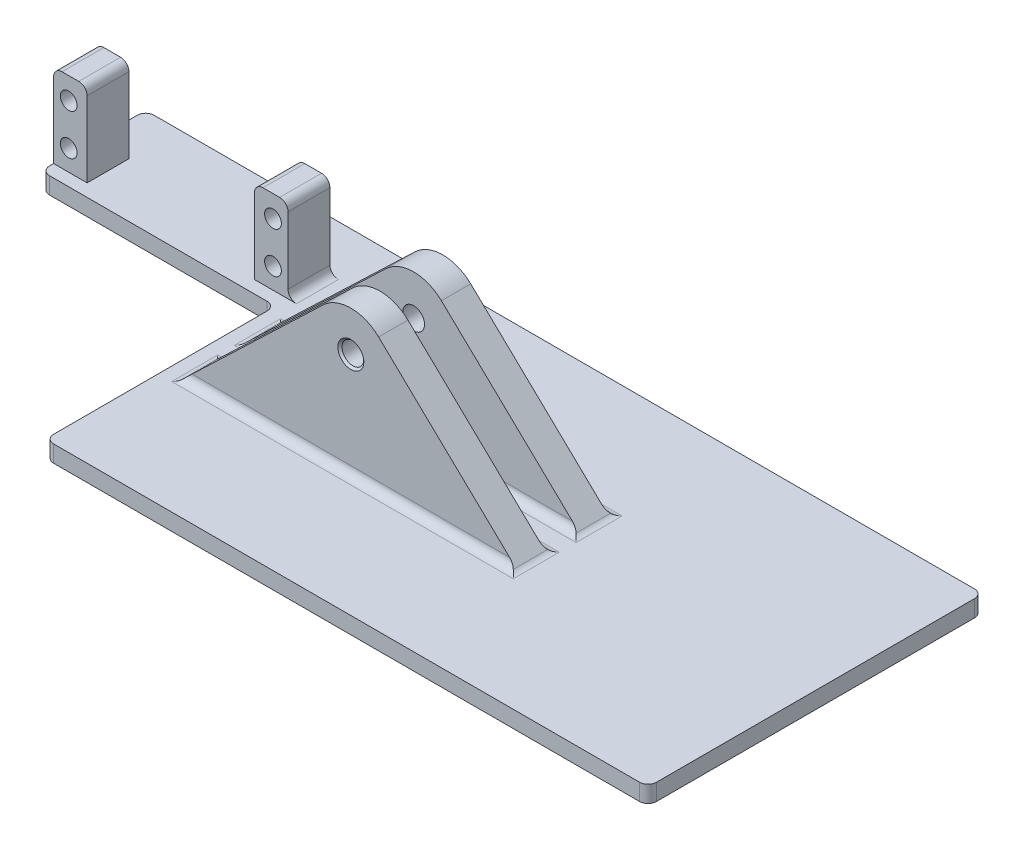
SolidWorks part; units mm, degrees
ref_plane "Front Plane" through (0, 0, 0) normal (0, 0, 1) x (1, 0, 0)
ref_plane "Top Plane" through (0, 0, 0) normal (0, 1, 0) x (1, 0, 0)
ref_plane "Right Plane" through (0, 0, 0) normal (1, 0, 0) x (0, 0, -1)
sketch "Sketch1" plane through (0, 0, 0) normal (0, 0, 1) x (1, 0, 0)
  line L0 (-6.6383, 6.9349) -> (-40, -25)
  line L1 (-40, -25) -> (40, -25)
  line L2 (40, -25) -> (6.6383, 6.9349)
  circle A0 centre (0, 0) radius 2.6
  arc A1 (6.6383, 6.9349) -> (-6.6383, 6.9349) centre (0, 0) ccw
  point P6 (0, -25)
  dimension "D1" = 5.2
  dimension "D2" = 7
  dimension "D3" = 80
  dimension "D4" = 25
extrude "Boss-Extrude1" add sketch "Sketch1" along normal blind 22
sketch "Sketch2" plane through (0, -25, 0) normal (0, -1, 0) x (-1, 0, 0)
  line L0 (-40, -22) -> (-40, 0) construction
  line L1 (-100, -51) -> (100, -51)
  line L2 (-100, -51) -> (-100, 29)
  line L3 (-100, 29) -> (100, 29)
  line L4 (100, -51) -> (100, 29)
  point P6 (-40, -11)
  point P7 (-100, -11)
  point P9 (0, 29)
  dimension "D1" = 200
  dimension "D2" = 80
extrude "Boss-Extrude2" add sketch "Sketch2" along normal blind 4
sketch "Sketch3" plane through (100, 0, 0) normal (1, 0, 0) x (0, 0, -1)
  line L0 (29, -25) -> (-51, -25) construction
  line L1 (-15, -25) -> (-7, -25)
  line L2 (-15, -25) -> (-15, 10)
  line L3 (-15, 10) -> (-7, 10)
  line L4 (-7, -25) -> (-7, 10)
  line L5 (0, -25) -> (0, 6.9349) construction
  dimension "D1" = 8
  dimension "D2" = 7
  dimension "D3" = 35
extrude "Cut-Extrude1" cut sketch "Sketch3" against normal through all
chamfer "Chamfer1" distance 0.5 angle 45 2 edges at (2.6, 0, 22) (2.6, 0, 0)
sketch "Sketch4" plane through (0, 0, -29) normal (0, 0, -1) x (-1, 0, 0)
  line L0 (72, -25) -> (72, 2.2972) construction
  line L1 (100, -25) -> (92, -25)
  line L2 (100, -25) -> (100, -5)
  line L3 (100, -5) -> (92, -5)
  line L4 (92, -25) -> (92, -5)
  line L5 (100, -25) -> (-100, -25) construction
  line L6 (44, -25) -> (52, -25)
  line L7 (52, -25) -> (52, -5)
  line L8 (44, -5) -> (52, -5)
  line L9 (44, -25) -> (44, -5)
  circle A0 centre (96.4, -20) radius 2
  circle A1 centre (96.4, -10.2) radius 2
  circle A2 centre (47.6, -20) radius 2
  circle A3 centre (47.6, -10.2) radius 2
  dimension "D4" = 4
  dimension "D5" = 5
  dimension "D1" = 8
  dimension "D2" = 20
  dimension "D3" = 9.8
  dimension "D6" = 4.4
  dimension "D7" = 20
extrude "Boss-Extrude3" add sketch "Sketch4" along normal blind 10 from offset 22 offset against normal yes
sketch "Sketch5" plane through (0, -25, 0) normal (0, 1, 0) x (1, 0, 0)
  line L0 (-44, 17) -> (-44, 7) construction
  line L1 (-100, -51) -> (-44, -51)
  line L2 (-100, -51) -> (-100, 4)
  line L3 (-100, 4) -> (-44, 4)
  line L4 (-44, -51) -> (-44, 4)
  dimension "D1" = 55
extrude "Cut-Extrude2" cut sketch "Sketch5" against normal blind 7
fillet "Fillet1" radius 2 19 edges at (-100, -5, -12) (-92, -5, -12) (-44, -5, -12) (-52, -5, -12) (-44, -25, -12) (0, -25, 0) (0, -25, 15) (-40, -25, 18.5) (0, -25, 7) (-40, -25, 3.5) (0, -25, 22) (40, -25, 3.5) (40, -25, 18.5) (100, -27, -29) (100, -27, 51) (-100, -27, -29) (-44, -27, -4) (-44, -27, 51) (-100, -27, -4)
